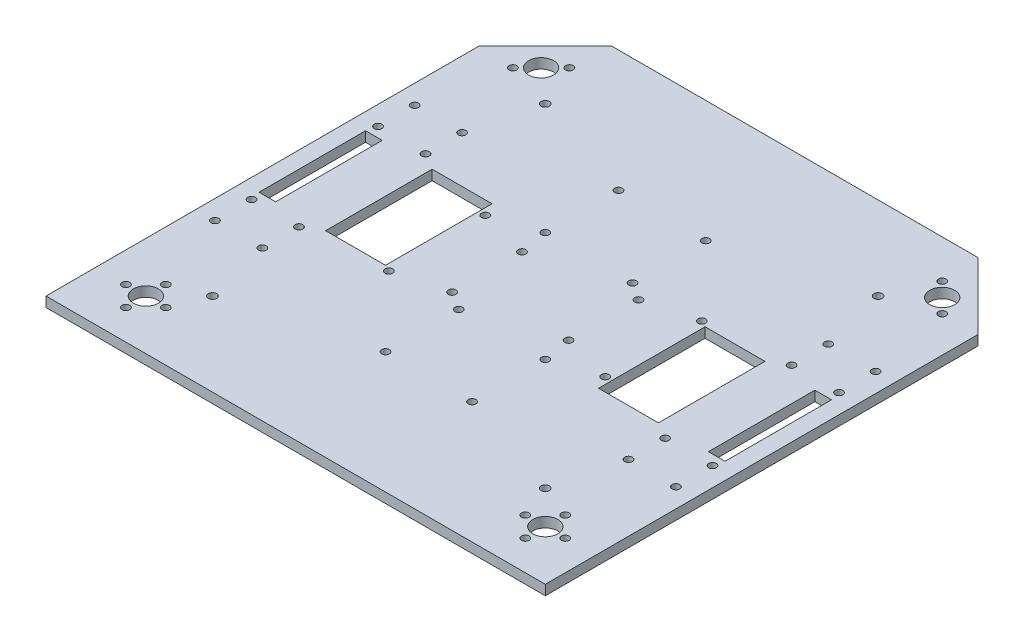
SolidWorks part; units mm, degrees
ref_plane "Plan de face" through (0, 0, 0) normal (0, 0, 1) x (1, 0, 0)
ref_plane "Plan de dessus" through (0, 0, 0) normal (0, 1, 0) x (1, 0, 0)
ref_plane "Plan de droite" through (0, 0, 0) normal (1, 0, 0) x (0, 0, -1)
sketch "Esquisse1" plane through (0, 0, 0) normal (0, 1, 0) x (1, 0, 0)
  line L0 (-150, 0) -> (-150, 260)
  line L2 (150, 0) -> (150, 260)
  line L3 (-150, 260) -> (-110, 260) construction
  line L4 (-110, 260) -> (-110, 300) construction
  line L5 (150, 260) -> (110, 260) construction
  line L6 (110, 260) -> (110, 300) construction
  line L8 (-150, 260) -> (-110, 300)
  line L9 (-110, 300) -> (110, 300)
  line L10 (0, 0) -> (0, 300) construction
  line L11 (110, 300) -> (150, 260)
  line L12 (-150, 0) -> (-120, 0) construction
  line L13 (-120, 18) -> (-120, 0) construction
  line L14 (150, 0) -> (120, 0) construction
  line L15 (120, 18) -> (120, 0) construction
  line L17 (-150, 260) -> (-120, 260) construction
  line L18 (-120, 260) -> (-120, 267.5) construction
  line L19 (150, 260) -> (120, 260) construction
  line L20 (120, 260) -> (120, 268.5) construction
  line L21 (-120, 267.5) -> (-111.5147, 275.9853) construction
  line L22 (-120, 267.5) -> (-128.4853, 259.0147) construction
  line L23 (120, 268.5) -> (128.4853, 260.0147) construction
  line L24 (120, 268.5) -> (111.5147, 276.9853) construction
  line L25 (-150, 0) -> (150, 0) construction
  line L26 (120, 30) -> (120, 18) construction
  line L27 (120, 30) -> (120, 42) construction
  line L28 (-150, 0) -> (150, 0)
  line L29 (-120, 18) -> (-120, 30) construction
  line L30 (-120, 30) -> (-120, 42) construction
  line L32 (150, 150) -> (-150, 150) construction
  line L33 (-120, 30) -> (-108, 30) construction
  line L34 (-120, 30) -> (-132, 30) construction
  line L35 (120, 30) -> (132, 30) construction
  line L36 (120, 30) -> (108, 30) construction
  circle A2 centre (-120, 30) radius 7.5
  circle A4 centre (-120, 267.5) radius 7.5
  circle A5 centre (120, 268.5) radius 7.5
  circle A6 centre (-111.5147, 275.9853) radius 2.3
  circle A7 centre (-128.4853, 259.0147) radius 2.3
  circle A8 centre (111.5147, 276.9853) radius 2.3
  circle A9 centre (128.4853, 260.0147) radius 2.3
  circle A10 centre (120, 30) radius 7.5
  circle A11 centre (120, 42) radius 2.3
  circle A13 centre (-120, 42) radius 2.3
  circle A14 centre (-120, 18) radius 2.3
  circle A16 centre (-132, 30) radius 2.3
  circle A17 centre (-108, 30) radius 2.3
  circle A18 centre (108, 30) radius 2.3
  circle A19 centre (132, 30) radius 2.3
  circle A20 centre (120, 18) radius 2.3
extrude "Boss.-Extru.1" add sketch "Esquisse1" along normal blind 6
sketch "Esquisse7" plane through (0, 6, 0) normal (0, 1, 0) x (1, 0, 0)
  line L0 (0, 150) -> (-130, 150) construction
  line L1 (0, 0) -> (0, 300) construction
  line L2 (150, 150) -> (-150, 150) construction
  line L3 (-130, 150) -> (-130, 182)
  line L4 (-130, 182) -> (-140, 182)
  line L5 (-140, 182) -> (-140, 118)
  line L6 (-140, 118) -> (-130, 118)
  line L7 (-130, 118) -> (-130, 150)
extrude "Enlèv. mat.-Extru.9" cut sketch "Esquisse7" against normal blind 10.5
sketch "Esquisse6" plane through (0, 6, 0) normal (0, 1, 0) x (1, 0, 0)
  line L0 (-142.5, 116) -> (-134.5, 116) construction
  line L2 (-142.5, 116) -> (-142.5, 150) construction
  line L3 (-142.5, 116) -> (-142.5, 108) construction
  line L11 (-142.5, 108) -> (-134.5, 108) construction
  line L12 (-134.5, 108) -> (-134.5, 116) construction
  line L14 (-142.5, 150) -> (-150, 150) construction
  line L15 (-142.5, 116) -> (-106, 116) construction
  line L16 (-106, 116) -> (-106, 108) construction
  line L17 (-106, 108) -> (-114, 108) construction
  line L18 (-114, 108) -> (-114, 116) construction
  line L19 (-114, 116) -> (-134.5, 116) construction
  line L20 (-134.5, 116) -> (-134.5, 86) construction
  line L21 (-134.5, 86) -> (-142.5, 86) construction
  line L22 (-142.5, 86) -> (-142.5, 94) construction
  line L23 (-142.5, 94) -> (-134.5, 94) construction
  line L24 (-134.5, 94) -> (-134.5, 86) construction
  line L25 (-134.5, 86) -> (-114, 86) construction
  line L26 (-114, 86) -> (-114, 94) construction
  line L27 (-114, 94) -> (-106, 94) construction
  line L28 (-106, 94) -> (-106, 86) construction
  line L29 (-106, 86) -> (-114, 86) construction
  line L30 (-106, 94) -> (-114, 86) construction
  line L31 (-114, 94) -> (-106, 86) construction
  line L32 (-142.5, 94) -> (-134.5, 86) construction
  line L33 (-142.5, 86) -> (-134.5, 94) construction
  line L34 (-142.5, 116) -> (-134.5, 108) construction
  line L35 (-142.5, 108) -> (-134.5, 116) construction
  line L38 (150, 150) -> (142.5, 150) construction
  line L39 (150, 150) -> (-150, 150) construction
  line L40 (142.5, 150) -> (142.5, 184) construction
  line L41 (142.5, 184) -> (142.5, 192) construction
  line L42 (142.5, 184) -> (134.5, 184) construction
  line L43 (134.5, 184) -> (134.5, 192) construction
  line L44 (134.5, 192) -> (142.5, 192) construction
  line L45 (142.5, 184) -> (106, 184) construction
  line L46 (106, 184) -> (106, 192) construction
  line L47 (106, 192) -> (114, 192) construction
  line L48 (114, 192) -> (114, 184) construction
  line L49 (114, 184) -> (134.5, 184) construction
  line L50 (114, 184) -> (114, 214) construction
  line L51 (114, 214) -> (134.5, 214) construction
  line L52 (134.5, 214) -> (134.5, 184) construction
  line L53 (114, 214) -> (106, 214) construction
  line L54 (106, 214) -> (106, 206) construction
  line L55 (106, 206) -> (114, 206) construction
  line L56 (114, 206) -> (106, 214) construction
  line L57 (106, 206) -> (114, 214) construction
  line L58 (134.5, 214) -> (142.5, 214) construction
  line L59 (142.5, 214) -> (142.5, 206) construction
  line L60 (142.5, 206) -> (134.5, 206) construction
  line L61 (134.5, 206) -> (142.5, 214) construction
  line L62 (134.5, 214) -> (142.5, 206) construction
  line L63 (134.5, 192) -> (142.5, 184) construction
  line L64 (142.5, 192) -> (134.5, 184) construction
  line L65 (106, 192) -> (114, 184) construction
  line L66 (106, 184) -> (114, 192) construction
  line L71 (-114, 116) -> (-106, 108) construction
  line L72 (-114, 108) -> (-106, 116) construction
  line L73 (-114, 116) -> (-114, 86) construction
  circle A16 centre (110, 210) radius 2.3
  circle A17 centre (138.5, 210) radius 2.3
  circle A18 centre (138.5, 188) radius 2.3
  circle A19 centre (110, 188) radius 2.3
  circle A20 centre (-138.5, 90) radius 2.3
  circle A21 centre (-138.5, 112) radius 2.3
  circle A22 centre (-110, 112) radius 2.3
  circle A23 centre (-110, 90) radius 2.3
  dimension "D3" = 34
  dimension "D4" = 7.5
  dimension "D1" = 7.5
  dimension "D2" = 34
sketch "Esquisse4" plane through (0, 6, 0) normal (0, 1, 0) x (1, 0, 0)
  line L0 (-150, 150) -> (-100, 150) construction
  line L8 (150, 150) -> (-150, 150) construction
  line L14 (-100, 150) -> (-100, 182)
  line L15 (-100, 250) -> (-100, 50) construction
  line L16 (-100, 150) -> (-100, 118)
  line L17 (-100, 118) -> (-64, 118)
  line L18 (-64, 118) -> (-64, 182)
  line L19 (-64, 182) -> (-100, 182)
sketch "Esquisse9" plane through (0, 6, 0) normal (0, 1, 0) x (1, 0, 0)
  line L0 (-150, 0) -> (150, 0) construction
  line L1 (150, 0) -> (150, 300) construction
  line L2 (150, 300) -> (-150, 300) construction
  line L3 (-150, 300) -> (-150, 0) construction
  line L5 (-150, 0) -> (-150, 300) construction
  line L6 (150, 0) -> (0, 0) construction
  line L7 (0, 0) -> (0, 50) construction
  line L8 (0, 0) -> (0, 300) construction
  line L9 (0, 50) -> (100, 50) construction
  line L10 (100, 50) -> (100, 250) construction
  line L11 (100, 250) -> (-100, 250) construction
  line L12 (-100, 250) -> (-100, 50) construction
  line L13 (-100, 50) -> (0, 50) construction
  line L18 (100, 250) -> (94.3431, 244.3431) construction
  line L21 (-150, 0) -> (150, 300) construction
  circle A0 centre (-100, 50) radius 2.5
  circle A1 centre (100, 50) radius 2.5
  circle A2 centre (100, 250) radius 2.5
  circle A3 centre (-100, 250) radius 2.5
extrude "Enlèv. mat.-Extru.10" cut sketch "Esquisse6" against normal blind 50
extrude "Enlèv. mat.-Extru.11" cut sketch "Esquisse4" against normal blind 50
sketch "Esquisse3" plane through (0, 6, 0) normal (0, 1, 0) x (1, 0, 0)
  line L6 (-150, 150) -> (-64, 150) construction
  line L7 (-64, 118) -> (-64, 182) construction
  line L8 (-64, 150) -> (-64, 178) construction
  line L9 (-64, 178) -> (-56, 178) construction
  line L10 (-56, 178) -> (-56, 170) construction
  line L11 (-56, 170) -> (-59, 170) construction
  line L16 (-64, 150) -> (-64, 112) construction
  line L17 (-64, 112) -> (-56, 112) construction
  line L25 (-56, 112) -> (-56, 120) construction
  line L26 (-64, 120) -> (-34, 120) construction
  line L27 (-56, 170) -> (-64, 178) construction
  line L28 (-64, 178) -> (-56, 178) construction
  line L29 (-56, 178) -> (-64, 170) construction
  line L30 (-34, 120) -> (-26, 120) construction
  line L31 (-56, 112) -> (-64, 120) construction
  line L32 (-64, 120) -> (-56, 120) construction
  line L33 (-56, 120) -> (-64, 112) construction
  line L37 (-26, 120) -> (-26, 128) construction
  line L38 (-26, 128) -> (-34, 128) construction
  line L39 (-34, 128) -> (-26, 120) construction
  line L43 (-26, 120) -> (-34, 120) construction
  line L55 (150, 150) -> (64, 150) construction
  line L56 (150, 150) -> (-150, 150) construction
  line L57 (64, 150) -> (64, 170) construction
  line L58 (34, 130) -> (26, 130) construction
  line L61 (64, 150) -> (64, 130) construction
  line L62 (64, 130) -> (59, 130) construction
  line L63 (59, 130) -> (59, 165) construction
  line L66 (59, 165) -> (39, 165) construction
  line L70 (39, 165) -> (39, 130) construction
  line L72 (39, 130) -> (34, 130) construction
  line L73 (34, 130) -> (34, 180) construction
  line L74 (34, 180) -> (64, 180) construction
  line L76 (64, 180) -> (64, 130) construction
  line L77 (-34, 120) -> (-26, 128) construction
  line L78 (26, 130) -> (26, 138) construction
  line L79 (-34, 120) -> (-34, 170) construction
  line L80 (-39, 170) -> (-34, 170) construction
  line L81 (-34, 170) -> (-26, 170) construction
  line L82 (-26, 170) -> (-26, 162) construction
  line L83 (-26, 162) -> (-34, 162) construction
  line L84 (-34, 162) -> (-26, 170) construction
  line L85 (-26, 170) -> (-34, 170) construction
  line L86 (-34, 170) -> (-26, 162) construction
  line L87 (26, 138) -> (34, 138) construction
  line L88 (-59, 170) -> (-59, 138) construction
  line L89 (-59, 138) -> (-39, 138) construction
  line L90 (-39, 138) -> (-39, 170) construction
  line L91 (34, 138) -> (26, 130) construction
  line L92 (26, 130) -> (26, 138) construction
  line L93 (26, 138) -> (34, 130) construction
  line L94 (34, 130) -> (34, 180) construction
  line L95 (34, 180) -> (26, 180) construction
  line L96 (26, 180) -> (26, 172) construction
  line L97 (26, 172) -> (34, 172) construction
  line L98 (34, 172) -> (26, 180) construction
  line L99 (26, 180) -> (26, 172) construction
  line L100 (26, 172) -> (34, 180) construction
  line L101 (64, 180) -> (64, 188) construction
  line L102 (64, 188) -> (56, 188) construction
  line L103 (56, 188) -> (56, 180) construction
  line L104 (56, 180) -> (64, 188) construction
  line L105 (64, 188) -> (56, 188) construction
  line L106 (56, 188) -> (64, 180) construction
  line L107 (64, 180) -> (64, 130) construction
  line L108 (64, 130) -> (64, 122) construction
  line L109 (64, 122) -> (56, 122) construction
  line L110 (56, 122) -> (56, 130) construction
  line L111 (56, 130) -> (59, 130) construction
  line L112 (64, 122) -> (56, 130) construction
  line L113 (56, 130) -> (56, 122) construction
  line L114 (56, 122) -> (64, 130) construction
  circle A8 centre (-60, 174) radius 2.3
  circle A10 centre (-60, 116) radius 2.3
  circle A12 centre (-30, 166) radius 2.3
  circle A13 centre (-30, 124) radius 2.3
  circle A14 centre (60, 184) radius 2.3
  circle A15 centre (30, 176) radius 2.3
  circle A16 centre (30, 134) radius 2.3
  circle A17 centre (60, 126) radius 2.3
mirror "Symétrie1" about plane through (0, 0, 0) normal (1, 0, 0) of "Enlèv. mat.-Extru.9"
mirror "Symétrie2" about plane through (0, 0, 0) normal (1, 0, 0) of "Enlèv. mat.-Extru.11"
mirror "Symétrie3" about plane through (0, 0, 0) normal (1, 0, 0) of "Enlèv. mat.-Extru.10"
extrude "Enlèv. mat.-Extru.12" cut sketch "Esquisse9" against normal blind 35
extrude "Enlèv. mat.-Extru.13" cut sketch "Esquisse3" against normal blind 35
sketch "Esquisse10" plane through (0, 6, 0) normal (0, 1, 0) x (1, 0, 0)
  line L0 (0, 150) -> (0, 205) construction
  line L1 (-37, 187) -> (-51.6, 187) construction
  line L2 (-37, 187) -> (-37, 223) construction
  line L3 (0, 113) -> (37, 113) construction
  line L4 (37, 113) -> (37, 77) construction
  line L5 (37, 77) -> (-23, 77) construction
  line L6 (-23, 77) -> (-23, 113) construction
  line L7 (-23, 113) -> (37, 113) construction
  line L8 (37, 113) -> (37, 69) construction
  line L9 (37, 69) -> (29, 69) construction
  line L10 (29, 69) -> (29, 77) construction
  line L11 (29, 77) -> (37, 69) construction
  line L12 (37, 69) -> (37, 77) construction
  line L13 (37, 77) -> (29, 69) construction
  line L14 (37, 113) -> (37, 121) construction
  line L15 (37, 121) -> (29, 121) construction
  line L16 (29, 121) -> (29, 113) construction
  line L17 (37, 95) -> (56.6, 95) construction
  line L18 (29, 69) -> (29, 77) construction
  line L19 (29, 113) -> (-23, 113) construction
  line L20 (29, 77) -> (-23, 77) construction
  line L21 (-23, 77) -> (-23, 69) construction
  line L22 (-23, 69) -> (-15, 69) construction
  line L23 (-15, 69) -> (-15, 77) construction
  line L24 (-37, 187) -> (-37, 179) construction
  line L25 (-37, 179) -> (-29, 179) construction
  line L26 (-15, 77) -> (-23, 69) construction
  line L27 (-23, 69) -> (-23, 77) construction
  line L28 (-23, 77) -> (-15, 69) construction
  line L29 (29, 113) -> (37, 121) construction
  line L30 (37, 121) -> (37, 113) construction
  line L31 (37, 113) -> (29, 121) construction
  line L32 (-23, 113) -> (-23, 121) construction
  line L33 (-23, 121) -> (-15, 121) construction
  line L34 (-15, 121) -> (-15, 113) construction
  line L35 (-29, 179) -> (-29, 187) construction
  line L36 (-37, 223) -> (23.4, 223) construction
  line L37 (23.4, 223) -> (23.4, 187) construction
  line L38 (23.4, 187) -> (-37, 187) construction
  line L39 (-37, 187) -> (23.4, 187) construction
  line L40 (23.4, 187) -> (23.4, 179) construction
  line L41 (23.4, 179) -> (15.4, 179) construction
  line L42 (0, 95) -> (37, 95) construction
  line L43 (-29, 187) -> (-37, 179) construction
  line L44 (-37, 179) -> (-37, 187) construction
  line L45 (-37, 187) -> (-29, 179) construction
  line L46 (-23, 121) -> (-15, 113) construction
  line L47 (0, 205) -> (-37, 205) construction
  line L48 (-15, 113) -> (-15, 121) construction
  line L49 (-15, 121) -> (-23, 113) construction
  line L50 (15.4, 179) -> (15.4, 187) construction
  line L51 (15.4, 187) -> (23.4, 179) construction
  line L52 (23.4, 179) -> (23.4, 187) construction
  line L53 (23.4, 187) -> (15.4, 179) construction
  line L54 (15.4, 179) -> (15.4, 187) construction
  line L55 (15.4, 187) -> (23.4, 187) construction
  line L56 (23.4, 187) -> (23.4, 223) construction
  line L57 (23.4, 223) -> (23.4, 231) construction
  line L58 (23.4, 231) -> (15.4, 231) construction
  line L59 (15.4, 231) -> (15.4, 223) construction
  line L60 (15.4, 223) -> (23.4, 231) construction
  line L61 (23.4, 231) -> (15.4, 231) construction
  line L62 (15.4, 231) -> (23.4, 223) construction
  line L73 (-52, 205) -> (-37, 205) construction
  line L78 (0, 0) -> (0, 300) construction
  line L79 (0, 150) -> (0, 95) construction
  line L80 (-37, 223) -> (-37, 231) construction
  line L83 (-20.6, 223) -> (-29, 223) construction
  line L84 (-29, 223) -> (-37, 231) construction
  line L85 (-37, 231) -> (-29, 231) construction
  line L89 (-29, 223) -> (-29, 231) construction
  line L90 (-29, 231) -> (-37, 223) construction
  circle A18 centre (-33, 227) radius 2.3
  circle A22 centre (-19, 73) radius 2.3
  circle A25 centre (33, 73) radius 2.3
  circle A26 centre (-33, 183) radius 2.3
  circle A29 centre (33, 117) radius 2.3
  circle A30 centre (-19, 117) radius 2.3
  circle A31 centre (19.4, 227) radius 2.3
  circle A32 centre (19.4, 183) radius 2.3
extrude "Enlèv. mat.-Extru.14" cut sketch "Esquisse10" against normal blind 10
sketch "Esquisse11" plane through (0, 6, 0) normal (0, 1, 0) x (1, 0, 0)
  line L0 (0, 150) -> (0, 185) construction
  line L1 (0, 0) -> (0, 300) construction
  line L2 (0, 185) -> (-30, 185) construction
  line L3 (-30, 185) -> (-30, 235) construction
  line L4 (-30, 185) -> (-30, 193) construction
  line L5 (0, 150) -> (0, 115) construction
  line L6 (0, 115) -> (30, 115) construction
  line L7 (30, 107) -> (30, 72) construction
  line L8 (30, 115) -> (30, 107) construction
  line L9 (-30, 223) -> (-38, 223) construction
  line L12 (-30, 213) -> (-38, 213) construction
  circle A7 centre (30, 97) radius 2.3
  circle A9 centre (30, 77) radius 2.3
  circle A11 centre (-30, 203) radius 2.3
  circle A13 centre (-30, 223) radius 2.3
  circle A17 centre (-30, 185) radius 2.3
  circle A18 centre (30, 115) radius 2.3
  circle A19 centre (-40, 223) radius 2.3
  circle A20 centre (-50, 223) radius 2.3
  circle A21 centre (40, 77) radius 2.3
  circle A22 centre (50, 77) radius 2.3
  dimension "D1" = 3
  dimension "D2" = 3
